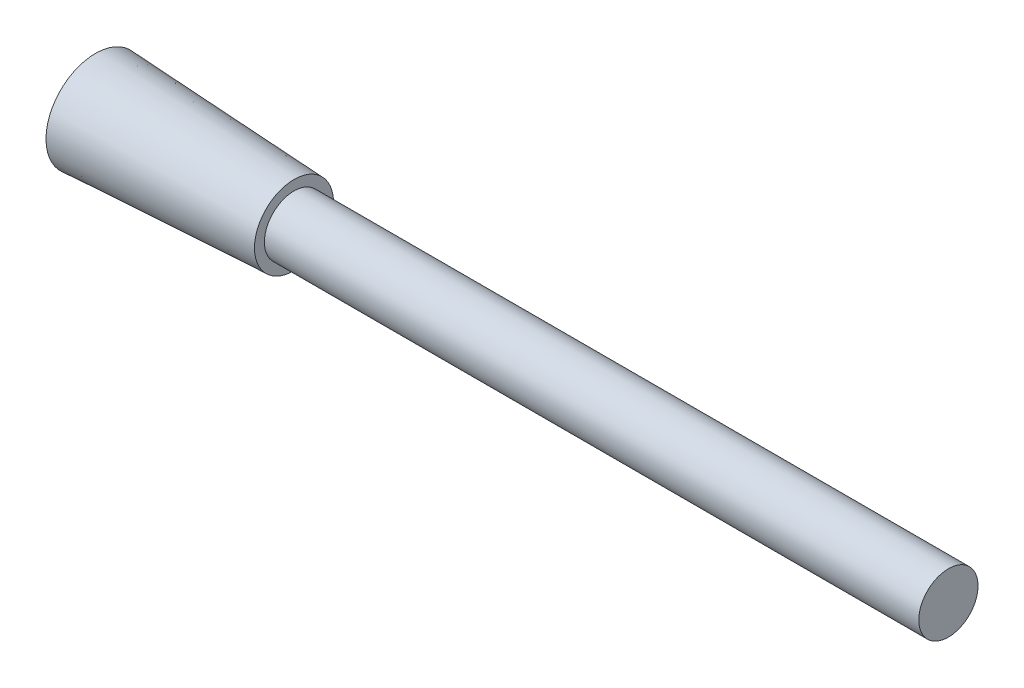
SolidWorks part; units mm, degrees
ref_plane "前视基准面" through (0, 0, 0) normal (0, 0, 1) x (1, 0, 0)
ref_plane "上视基准面" through (0, 0, 0) normal (0, 1, 0) x (1, 0, 0)
ref_plane "右视基准面" through (0, 0, 0) normal (1, 0, 0) x (0, 0, -1)
other "Configuration Table"
sketch "草图1" plane through (0, 0, 0) normal (0, 1, 0) x (1, 0, 0)
  line L0 (0, 0) -> (525, 0) construction
  line L1 (525, 0) -> (525, -890) construction
  line L2 (525, -890) -> (840.486, -890) construction
  line L3 (525, -890) -> (525, -897.5)
  line L4 (525, -897.5) -> (555.1445, -896)
  line L5 (555.1445, -896) -> (555.1445, -894.5)
  line L6 (555.1445, -894.5) -> (654.4746, -894.5)
  line L7 (654.4746, -894.5) -> (654.4746, -890)
  line L8 (654.4746, -890) -> (525, -890)
  point P9 (605.0493, 882.5)
  point P11 (555.1445, 884)
  dimension "D1" = 525
  dimension "D2" = 890
  dimension "D3" = 7.5
  dimension "D4" = 6
  dimension "D5" = 4.5
revolve "旋转1" add sketch "草图1" angle 360 about L2
